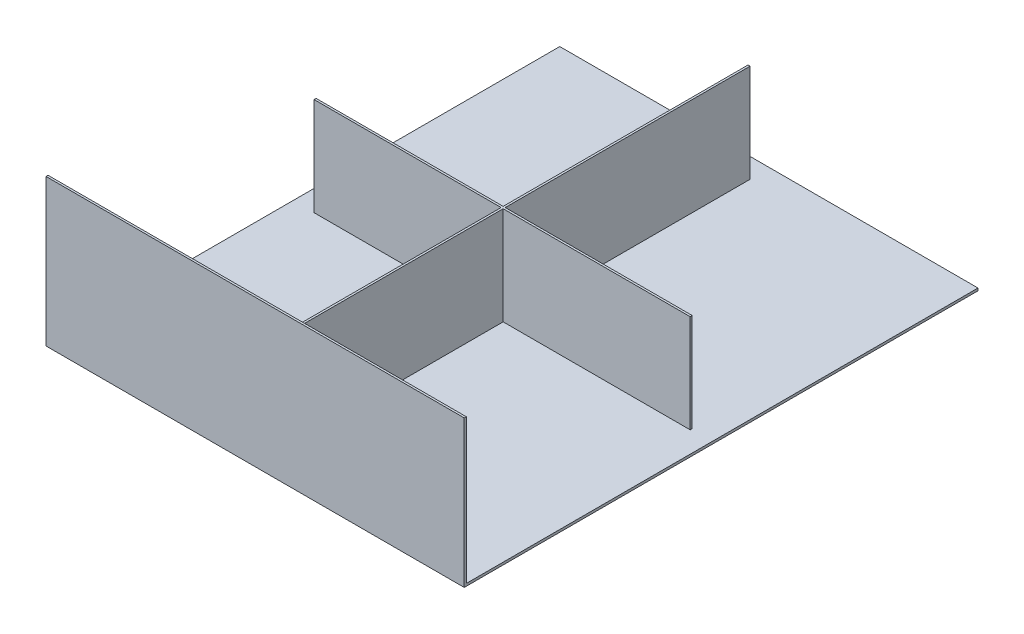
SolidWorks part; units mm, degrees
material "Custom Plastic"
ref_plane "Front Plane" through (0, 0, 0) normal (0, 0, 1) x (1, 0, 0)
ref_plane "Top Plane" through (0, 0, 0) normal (0, 1, 0) x (1, 0, 0)
ref_plane "Right Plane" through (0, 0, 0) normal (1, 0, 0) x (0, 0, -1)
sketch "Sketch1" plane through (0, 0, 0) normal (0, 1, 0) x (1, 0, 0)
  line L0 (-225.35, -266.2) -> (-225.35, 287.45)
  line L1 (204.1, -266.2) -> (-204.1, -266.2)
  line L2 (204.1, -266.2) -> (204.1, 266.2) construction
  line L3 (204.1, 266.2) -> (-204.1, 266.2) construction
  line L4 (-204.1, -266.2) -> (-204.1, 266.2) construction
  line L5 (204.1, -266.2) -> (-204.1, 266.2) construction
  line L6 (204.1, 266.2) -> (-204.1, -266.2) construction
  line L7 (225.35, 287.45) -> (-225.35, 287.45)
  line L8 (225.35, -266.2) -> (225.35, 287.45)
  line L9 (-204.1, -266.2) -> (-225.35, -266.2)
  line L10 (204.1, -266.2) -> (225.35, -266.2)
  point P0 (0, 0)
  dimension "D1" = 532.4
  dimension "D2" = 408.2
  dimension "D3" = 21.25
extrude "Boss-Extrude1" add sketch "Sketch1" along normal blind 2.64 contours L4 L3 L2 L1
sketch "Sketch2" plane through (0, 2.64, 0) normal (0, 1, 0) x (1, 0, 0)
  line L1 (-225.35, -266.2) -> (225.35, -266.2)
  line L2 (-225.35, -266.2) -> (-225.35, -264)
  line L3 (-225.35, -264) -> (225.35, -264)
  line L4 (225.35, -266.2) -> (225.35, -264)
  line L5 (225.35, -266.2) -> (225.35, 287.45) construction
  line L6 (-225.35, 287.45) -> (-225.35, -266.2) construction
  line L7 (-225.35, -266.2) -> (225.35, -266.2) construction
  dimension "D1" = 2.2
extrude "Boss-Extrude2" add sketch "Sketch2" along normal blind 155.6
sketch "Sketch3" plane through (0, 2.64, 0) normal (0, 1, 0) x (1, 0, 0)
  line L0 (0, -264) -> (0, 266.2) construction
  line L1 (225.35, -264) -> (-225.35, -264) construction
  line L2 (-202.6, 1.1) -> (202.6, 1.1) construction
  line L3 (1.1, -264) -> (1.1, 0)
  line L4 (-202.6, 0) -> (-1.1, 0)
  line L5 (-1.1, -264) -> (-1.1, 0)
  line L6 (-202.6, 2.2) -> (-1.1, 2.2)
  line L7 (1.1, -264) -> (-1.1, -264)
  line L8 (1.1, 266.2) -> (-1.1, 266.2)
  line L9 (-202.6, 0) -> (-202.6, 2.2)
  line L10 (202.6, 0) -> (202.6, 2.2)
  line L11 (1.1, 2.2) -> (1.1, 266.2)
  line L12 (1.1, -264) -> (1.1, 266.2) construction
  line L13 (1.1, 0) -> (202.6, 0)
  line L14 (-202.6, 0) -> (202.6, 0) construction
  line L15 (-1.1, 2.2) -> (-1.1, 266.2)
  line L16 (-1.1, -264) -> (-1.1, 266.2) construction
  line L17 (1.1, 2.2) -> (202.6, 2.2)
  line L18 (-202.6, 2.2) -> (202.6, 2.2) construction
  dimension "D1" = 405.2
  dimension "D2" = 530.2
  dimension "D5" = 265.1
  dimension "D3" = 1.1
  dimension "D4" = 1.1
extrude "Boss-Extrude3" add sketch "Sketch3" along normal blind 105.6
equation "\"D1@Sketch1\"=261mm*2+6mm+2.2mm*2"
equation "\"D2@Sketch1\"=200mm*2+2.2mm+6mm"
equation "\"D1@Boss-Extrude2\"=52.8mm*2+50mm"
equation "\"D1@Sketch3\"=200*2+2.2+3"
equation "\"D2@Sketch3\"=261*2+2.2+6"
equation "\"D1@Boss-Extrude3\"=52.8*2"
equation "\"D5@Sketch3\"=261+3+1.1"
